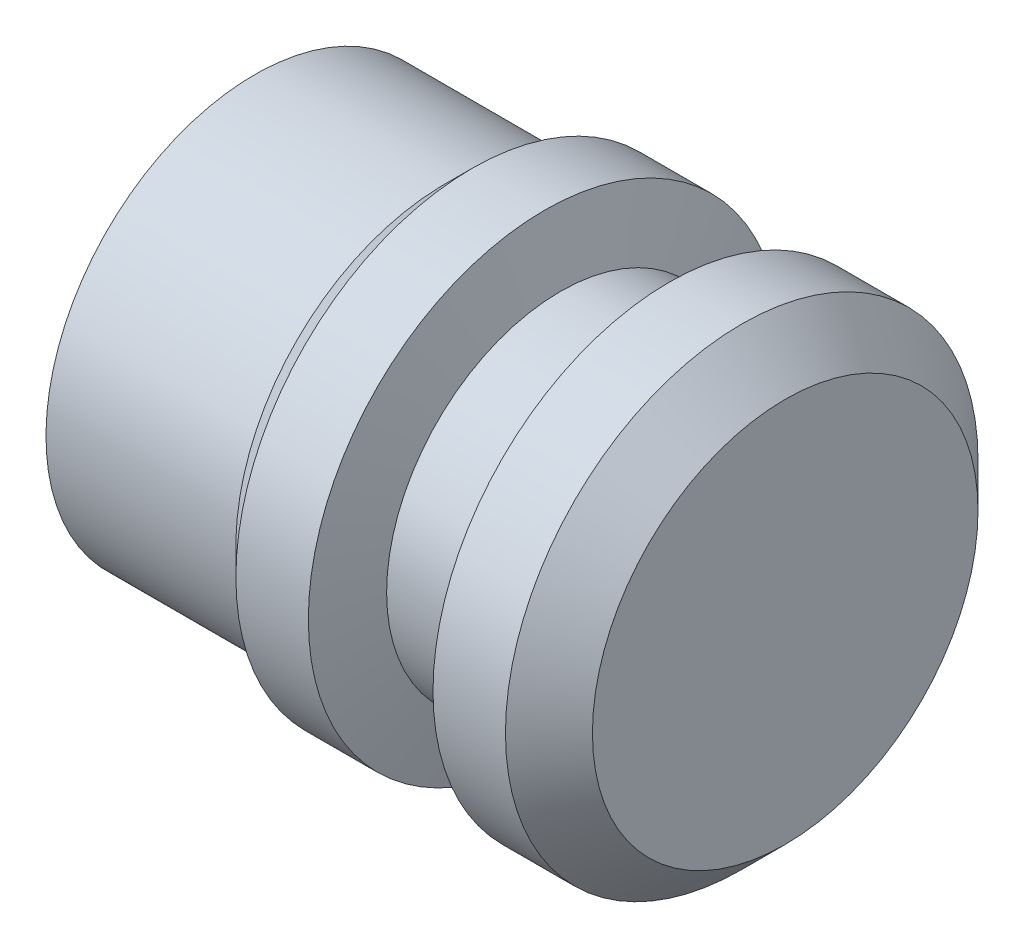
SolidWorks part; units mm, degrees
ref_plane "Front Plane" through (0, 0, 0) normal (0, 0, 1) x (1, 0, 0)
ref_plane "Top Plane" through (0, 0, 0) normal (0, 1, 0) x (1, 0, 0)
ref_plane "Right Plane" through (0, 0, 0) normal (1, 0, 0) x (0, 0, -1)
sketch "Sketch1" plane through (0, 0, 0) normal (0, 1, 0) x (1, 0, 0)
  line L0 (-23.013, 0) -> (32.9424, 0)
  line L1 (-6.15, 0) -> (0, 0)
  line L2 (0, 0) -> (0, 4.075)
  line L3 (0, 4.075) -> (-2, 4.075)
  line L4 (-2, 4.075) -> (-2.275, 3)
  line L5 (-2.275, 3) -> (-3.875, 3)
  line L6 (-3.875, 3) -> (-4.15, 4.075)
  line L7 (-4.15, 4.075) -> (-6.15, 4.075)
  line L8 (-6.15, 4.075) -> (-6.15, 0)
  dimension "D1" = 6.15
  dimension "D2" = 4.075
  dimension "D3" = 0
  dimension "D4" = 3
  dimension "D5" = 0
  dimension "D6" = 2
  dimension "D7" = 2
  dimension "D8" = 1.6
  dimension "D9" = 0.275
  dimension "D10" = 0
revolve "Revolve1" add sketch "Sketch1" angle 360 about L0
chamfer "Chamfer1" distance 0.75 angle 45 2 edges at (0, 0, 4.075) (-6.15, 0, 4.075)
sketch "Sketch2" plane through (-6.15, 0, 0) normal (-1, 0, 0) x (0, 0, 1)
  circle A0 centre (0, 0) radius 3.6
  dimension "D1" = 7.2
extrude "Boss-Extrude1" add sketch "Sketch2" along normal blind 3 and the other way blind 1
sketch "Sketch3" plane through (-9.15, 0, 0) normal (-1, 0, 0) x (0, 0, 1)
  circle A0 centre (0, 0) radius 0.55
  dimension "D1" = 1.1
extrude "Boss-Extrude2" add sketch "Sketch3" along normal blind 2
sketch "Sketch4" plane through (-9.15, 0, 0) normal (-1, 0, 0) x (0, 0, 1)
  line L0 (0, 0) -> (0, -3.6)
  line L1 (0, 0) -> (-3.2277, -1.5944)
  circle A0 centre (0, 0) radius 2.05
  circle A1 centre (0, 0) radius 3.6
  circle M1 centre (0, 0) radius 3.6
  dimension "D1" = 4.1
  dimension "D2" = 7.2
  dimension "D3" = 3.8
extrude "Cut-Extrude1" cut sketch "Sketch4" against normal blind 2.5 contours A0 L1 L0 M1
